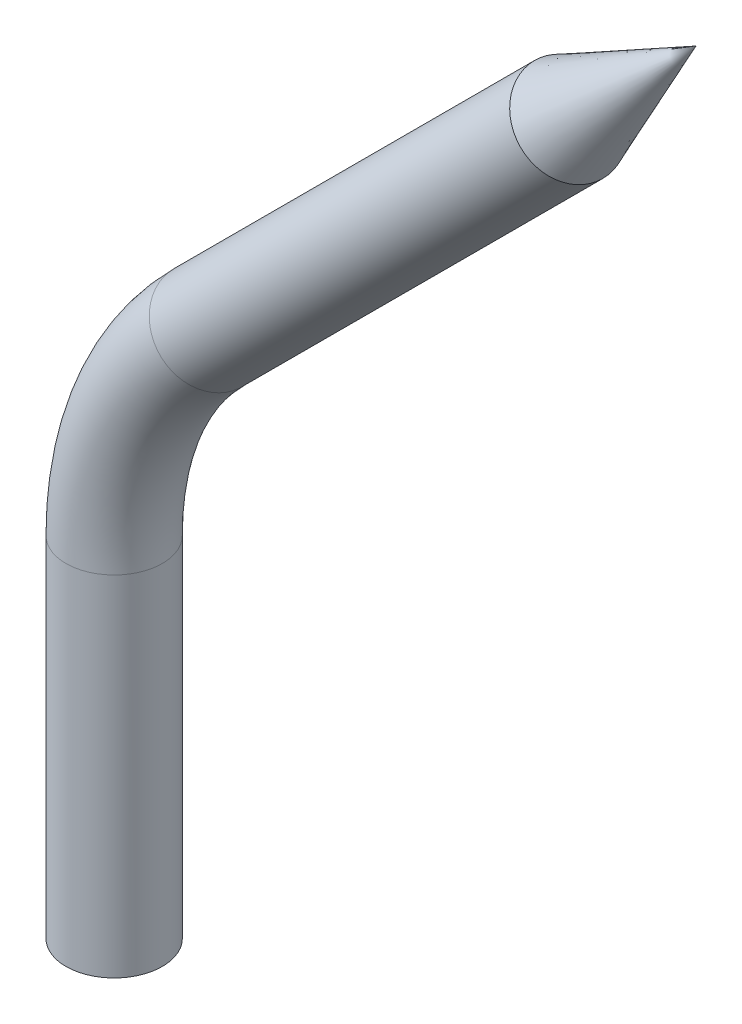
SolidWorks part; units mm, degrees
material "Chrome Stainless Steel"
ref_plane "Front Plane" through (0, 0, 0) normal (0, 0, 1) x (1, 0, 0)
ref_plane "Top Plane" through (0, 0, 0) normal (0, 1, 0) x (1, 0, 0)
ref_plane "Right Plane" through (0, 0, 0) normal (1, 0, 0) x (0, 0, -1)
sketch "Sketch7" plane through (0, 0, 0) normal (0, 0, 1) x (1, 0, 0)
  line L0 (0, 0) -> (0, 24.1716)
  line L1 (0.5858, 25.5858) -> (2.8284, 27.8284)
  arc A0 (0, 24.1716) -> (0.5858, 25.5858) centre (2, 24.1716) cw
  point P6 (0, 25)
  dimension "D4" = 2
  dimension "D1" = 25
  dimension "D2" = 4
  dimension "D3" = 45
sketch "Sketch8" plane through (0, 0, 0) normal (0, 1, 0) x (1, 0, 0)
  circle A1 centre (0, 0) radius 0.3
  dimension "D2" = 0.6
sweep "Sweep1" add profiles "Sketch8" path "Sketch7"
sketch "Sketch9" plane through (0, 0, 0) normal (0, 0, 1) x (1, 0, 0)
  line L0 (3.0406, 27.6163) -> (2.6163, 28.0406) construction
  line L1 (3.0406, 27.6163) -> (2.6163, 28.0406) construction
  line L2 (2.2854, 27.2854) -> (3.1515, 28.1515) construction
  line L3 (2.6163, 28.0406) -> (3.6201, 28.6201)
  line L4 (3.6201, 28.6201) -> (2.8284, 27.8284)
  line L5 (2.8284, 27.8284) -> (2.6163, 28.0406)
  point P3 (2.8284, 27.8284)
  dimension "D1" = 15
revolve "Revolve2" add sketch "Sketch9" angle 360 about L2
sketch "Sketch10" plane through (0, 0, 0) normal (0, 0, 1) x (1, 0, 0)
  line L1 (-2.5, -22) -> (2.5, -22)
  line L2 (-2.5, -22) -> (-2.5, 22)
  line L3 (-2.5, 22) -> (2.5, 22)
  line L4 (2.5, -22) -> (2.5, 22)
  line L5 (-2.5, -22) -> (2.5, 22) construction
  line L6 (-2.5, 22) -> (2.5, -22) construction
  point P0 (0, 0)
  dimension "D1" = 22
  dimension "D2" = 5
extrude "Cut-Extrude1" cut sketch "Sketch10" against normal through all and the other way through all
